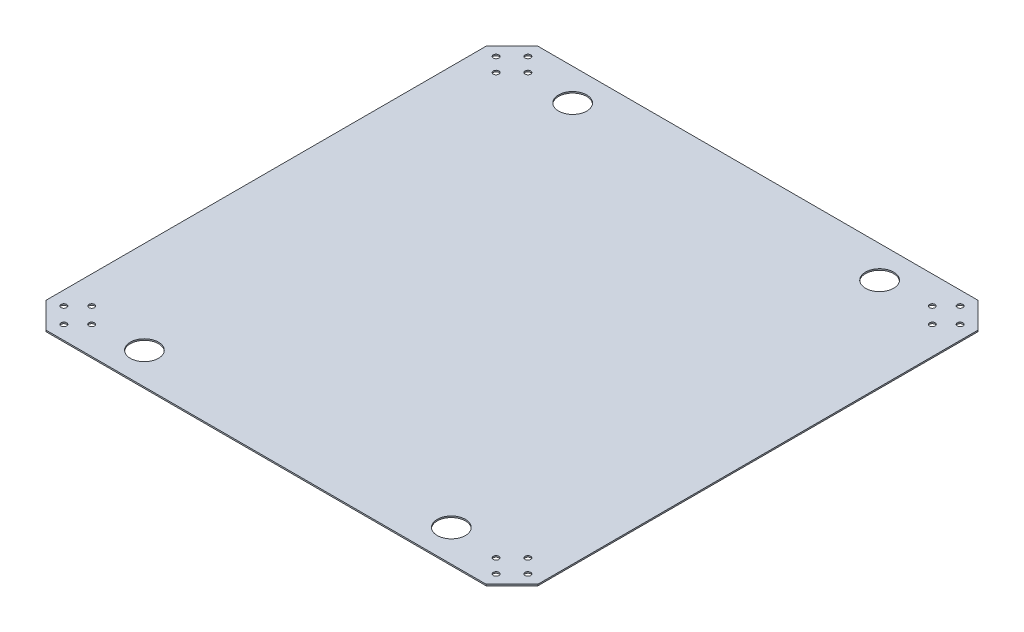
SolidWorks part; units mm, degrees
ref_plane "Front Plane" through (0, 0, 0) normal (0, 0, 1) x (1, 0, 0)
ref_plane "Top Plane" through (0, 0, 0) normal (0, 1, 0) x (1, 0, 0)
ref_plane "Right Plane" through (0, 0, 0) normal (1, 0, 0) x (0, 0, -1)
sketch "Sketch2" plane through (0, 0, 0) normal (0, 1, 0) x (1, 0, 0)
  line L1 (-156.615, 175) -> (156.615, 175)
  line L2 (-175, 156.615) -> (-175, -156.615)
  line L3 (-156.615, -175) -> (156.615, -175)
  line L4 (175, 156.615) -> (175, -156.615)
  line L5 (-165.8075, 165.8075) -> (165.8075, -165.8075) construction
  line L6 (-165.8075, -165.8075) -> (165.8075, 165.8075) construction
  line L8 (-156.615, 175) -> (-175, 156.615)
  line L11 (-175, -156.615) -> (-156.615, -175)
  line L13 (-175, 156.615) -> (-152.3726, 133.9876)
  line L14 (-156.615, 175) -> (-133.9876, 152.3726)
  line L15 (-152.3726, 133.9876) -> (-133.9876, 152.3726)
  line L16 (175, 156.615) -> (156.615, 175)
  line L18 (156.615, 175) -> (133.9876, 152.3726)
  line L19 (175, 156.615) -> (152.3726, 133.9876)
  line L20 (133.9876, 152.3726) -> (152.3726, 133.9876)
  line L21 (156.615, -175) -> (175, -156.615)
  line L23 (175, -156.615) -> (152.3726, -133.9876)
  line L24 (156.615, -175) -> (133.9876, -152.3726)
  line L25 (152.3726, -133.9876) -> (133.9876, -152.3726)
  line L28 (-156.615, -175) -> (-133.9876, -152.3726)
  line L29 (-175, -156.615) -> (-152.3726, -133.9876)
  line L30 (-133.9876, -152.3726) -> (-152.3726, -133.9876)
  line L31 (175, 156.615) -> (156.615, 175) [skipped]
  line L32 (156.615, -175) -> (175, -156.615) [skipped]
  line L33 (-175, -156.615) -> (-156.615, -175) [skipped]
  circle A0 centre (-165.1005, 153.7866) radius 2
  circle A1 centre (-153.7866, 165.1005) radius 2
  circle A2 centre (-155.201, 143.8871) radius 2
  circle A3 centre (-143.8873, 155.2008) radius 2
  circle A4 centre (153.7866, 165.1005) radius 2
  circle A5 centre (165.1005, 153.7866) radius 2
  circle A6 centre (143.8871, 155.201) radius 2
  circle A7 centre (155.2008, 143.8873) radius 2
  circle A8 centre (165.1005, -153.7866) radius 2
  circle A9 centre (153.7866, -165.1005) radius 2
  circle A10 centre (155.201, -143.8871) radius 2
  circle A11 centre (143.8873, -155.2008) radius 2
  circle A12 centre (-153.7866, -165.1005) radius 2
  circle A13 centre (-165.1005, -153.7866) radius 2
  circle A14 centre (-143.8871, -155.201) radius 2
  circle A15 centre (-155.2008, -143.8873) radius 2
  circle A16 centre (-109.2041, 152.3726) radius 10
  circle A17 centre (109.2041, 152.3726) radius 10
  circle A18 centre (109.2041, -152.3726) radius 10
  circle A19 centre (-109.2041, -152.3726) radius 10
  point P0 (0, 0)
  point P17 (0, 0)
  point P64 (0, 0)
  dimension "D3" = 350
  dimension "D7" = 14
  dimension "D9" = 16.0003
  dimension "D12" = 350
  dimension "D13" = 20
  dimension "D1" = 4
  dimension "D2" = 313.23
  dimension "D4" = 26.0003
  dimension "D5" = 4
  dimension "D6" = 9
  dimension "D8" = 5
  dimension "D10" = 5
  dimension "D11" = 313.23
extrude "Boss-Extrude3" add sketch "Sketch2" along normal blind 1 contours L30 L28 L3 L24 L25 L23 L4 L19 L20 L18 L1 L14 L15 L13 L2 L29 | L13 L15 L14 L8 A3 A2 A1 A0 | L28 L30 L29 L11 A15 A14 A13 A12 | L23 L25 L24 L21 A11 A10 A9 A8 | L18 L20 L19 L16 A7 A6 A5 A4
